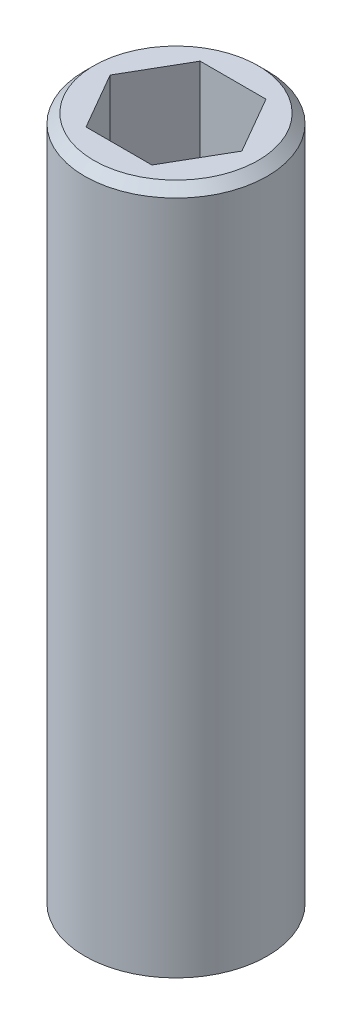
SolidWorks part; units mm, degrees
material "Brass"
ref_plane "Front Plane" through (0, 0, 0) normal (0, 0, 1) x (1, 0, 0)
ref_plane "Top Plane" through (0, 0, 0) normal (0, 1, 0) x (1, 0, 0)
ref_plane "Right Plane" through (0, 0, 0) normal (1, 0, 0) x (0, 0, -1)
sketch "Sketch1" plane through (0, 0, 0) normal (0, 1, 0) x (1, 0, 0)
  circle A0 centre (0, 0) radius 2
  dimension "D1" = 4
extrude "Boss-Extrude1" add sketch "Sketch1" along normal mid plane 15
cosmetic thread "Cosmetic Thread1" parameters "D1"=5.5, "D2"=3.22
sketch "Sketch2" plane through (0, 7.5, 0) normal (0, 1, 0) x (1, 0, 0)
  line L1 (0.7217, 1.25) -> (-0.7217, 1.25)
  line L2 (-0.7217, 1.25) -> (-1.4434, 0)
  line L3 (-1.4434, 0) -> (-0.7217, -1.25)
  line L4 (-0.7217, -1.25) -> (0.7217, -1.25)
  line L5 (0.7217, -1.25) -> (1.4434, 0)
  line L6 (1.4434, 0) -> (0.7217, 1.25)
  circle A0 centre (0, 0) radius 1.25 construction
  dimension "D1" = 2.5
extrude "Cut-Extrude1" cut sketch "Sketch2" against normal blind 2
chamfer "Chamfer1" distance 0.2 angle 45 1 edges at (0, 7.5, 2)
